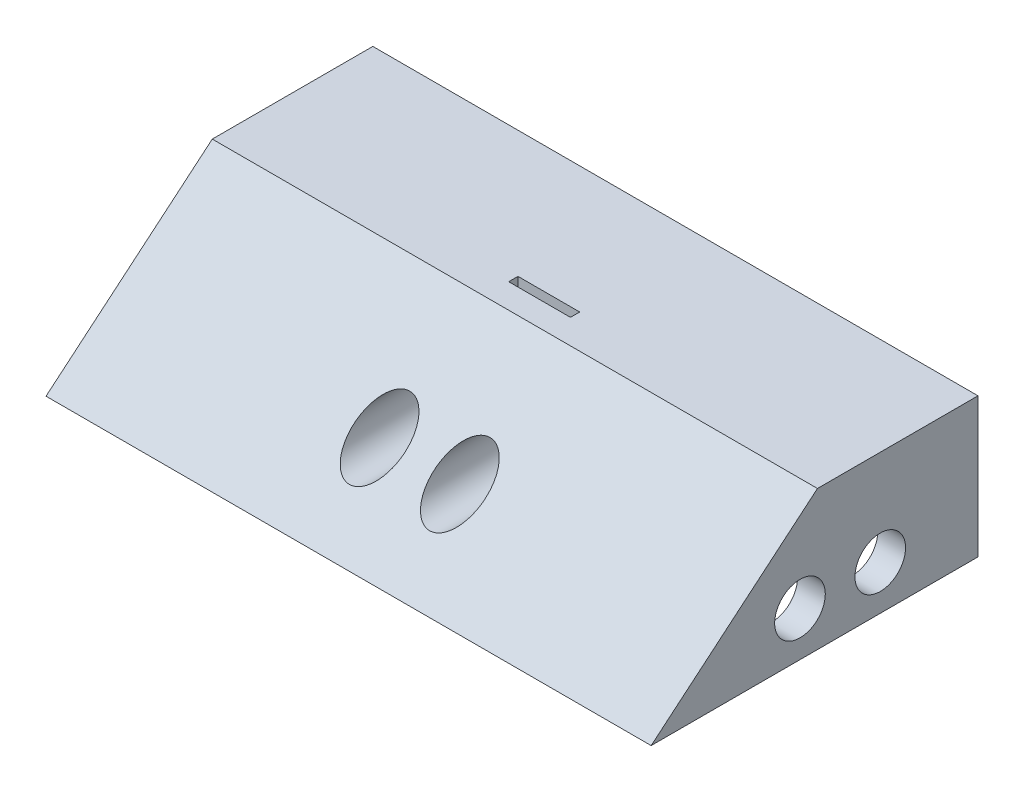
SolidWorks part; units mm, degrees
ref_plane "Alzado" through (0, 0, 0) normal (0, 0, 1) x (1, 0, 0)
ref_plane "Planta" through (0, 0, 0) normal (0, 1, 0) x (1, 0, 0)
ref_plane "Vista lateral" through (0, 0, 0) normal (1, 0, 0) x (0, 0, -1)
sketch "Croquis1" plane through (0, 0, 0) normal (1, 0, 0) x (0, 0, -1)
  line L0 (0, 0) -> (105.85, 0)
  line L1 (105.85, 0) -> (105.85, 45.19)
  line L2 (105.85, 45.19) -> (53.8553, 45.19)
  line L3 (0, 0) -> (53.8553, 45.19)
  line L4 (105.8531, 0) -> (105.8531, 45.19) construction
  line L5 (105.85, 0) -> (0, 0) construction
  line L6 (53.8553, 45.19) -> (105.85, 45.19) construction
  dimension "D1" = 105.85
  dimension "D2" = 45.19
  dimension "D3" = 140
extrude "Saliente-Extruir1" add sketch "Croquis1" along normal blind 196
shell "Vaciado1" thickness 4
sketch "Croquis2" plane through (196, 0, 0) normal (1, 0, 0) x (0, 0, -1)
  line L0 (-21.1601, -5.67) -> (105.85, -5.67) construction
  line L2 (53.8553, 45.19) -> (0, 0) construction
  circle A0 centre (48.1923, 14.33) radius 8.2
  circle A1 centre (74.1923, 14.33) radius 8.2
  dimension "D1" = 16.4
  dimension "D2" = 16.4
  dimension "D3" = 26
  dimension "D4" = 20
  dimension "D5" = 20
extrude "Cortar-Extruir1" cut sketch "Croquis2" against normal blind 4
sketch "Croquis3" plane through (196, 0, 0) normal (1, 0, 0) x (0, 0, -1)
  circle A0 centre (48.1923, 14.33) radius 8.2
  circle A1 centre (74.1923, 14.33) radius 8.2
  circle A2 centre (48.1923, 14.33) radius 9.2
  circle A3 centre (74.1923, 14.33) radius 9.2
  dimension "D1" = 16.4
  dimension "D2" = 16.4
  dimension "D3" = 18.4
  dimension "D4" = 18.4
extrude "Saliente-Extruir2" add sketch "Croquis3" against normal blind 9
fillet "Redondeo3" radius 3 2 edges at (192, 14.33, -83.3923) (192, 14.33, -57.3923)
ref_plane "Plano1" through (98, 0, 0) normal (1, 0, 0) x (0, 0, -1)
mirror "Simetría1" about plane through (98, 0, 0) normal (1, 0, 0) of "Saliente-Extruir2", "Cortar-Extruir1"
fillet "Redondeo4" radius 3 2 edges at (4, 14.33, -83.3923) (4, 14.33, -57.3923)
ref_plane "Plano2" through (0, 0, 0) normal (0, 0, 1) x (1, 0, 0)
sketch "Croquis4" plane through (0, 0, 0) normal (0, 0, 1) x (1, 0, 0)
  line L0 (98, -24.8545) -> (98, 24.8545) construction
  line L1 (196, -5.67) -> (0, -5.67) construction
  circle A0 centre (85, 19.33) radius 8.2
  circle A1 centre (111, 19.33) radius 8.2
  point P10 (116.927, 23.0606)
  dimension "D1" = 16.4
  dimension "D4" = 16.4
  dimension "D2" = 13
  dimension "D3" = 25
  dimension "D5" = 13
  dimension "D6" = 25
extrude "Cortar-Extruir2" cut sketch "Croquis4" against normal up to next
sketch "Croquis5" plane through (0, 0, 0) normal (0, 0, 1) x (1, 0, 0)
  circle A0 centre (85, 19.33) radius 8.2
  circle A1 centre (111, 19.33) radius 8.2
  circle A2 centre (111, 19.33) radius 9.2
  circle A3 centre (85, 19.33) radius 9.2
  dimension "D1" = 16.4
  dimension "D2" = 16.4
  dimension "D3" = 18.4
  dimension "D4" = 18.4
extrude "Saliente-Extruir3" add sketch "Croquis5" against normal blind 43
ref_plane "Plano3" through (0, 0, 0) normal (0, 0.766, 0.6428) x (1, 0, 0)
sketch "Croquis6" plane through (0, 0, 0) normal (0, 0.766, 0.6428) x (1, 0, 0)
  line L1 (57.9143, 48.3946) -> (140.7881, 48.3946)
  line L2 (57.9143, 48.3946) -> (57.9143, 4.7057)
  line L3 (57.9143, 4.7057) -> (140.7881, 4.7057)
  line L4 (140.7881, 48.3946) -> (140.7881, 4.7057)
  line L5 (57.9143, 48.3946) -> (140.7881, 4.7057) construction
  line L6 (57.9143, 4.7057) -> (140.7881, 48.3946) construction
  point P4 (99.3512, 26.5502)
extrude "Cortar-Extruir3" cut sketch "Croquis6" along normal up to next
sketch "Croquis9" plane through (0, 45.19, 0) normal (0, 1, 0) x (1, 0, 0)
  line L0 (196, 53.8553) -> (0, 53.8553) construction
  line L1 (88, 61.8553) -> (108, 61.8553)
  line L2 (88, 61.8553) -> (88, 64.8553)
  line L3 (88, 64.8553) -> (108, 64.8553)
  line L4 (108, 61.8553) -> (108, 64.8553)
  line L5 (88, 61.8553) -> (108, 64.8553) construction
  line L6 (88, 64.8553) -> (108, 61.8553) construction
  line L7 (0, 53.8553) -> (196, 53.8553) construction
  line L8 (98, 53.8553) -> (98, 72.5545) construction
  point P4 (108, 63.3553)
  point P7 (93.2604, 61.8553)
  point P14 (88.5762, 61.8553)
  dimension "D1" = 8
  dimension "D2" = 3
  dimension "D3" = 20
  dimension "D4" = 10
extrude "Cortar-Extruir4" cut sketch "Croquis9" against normal up to next
